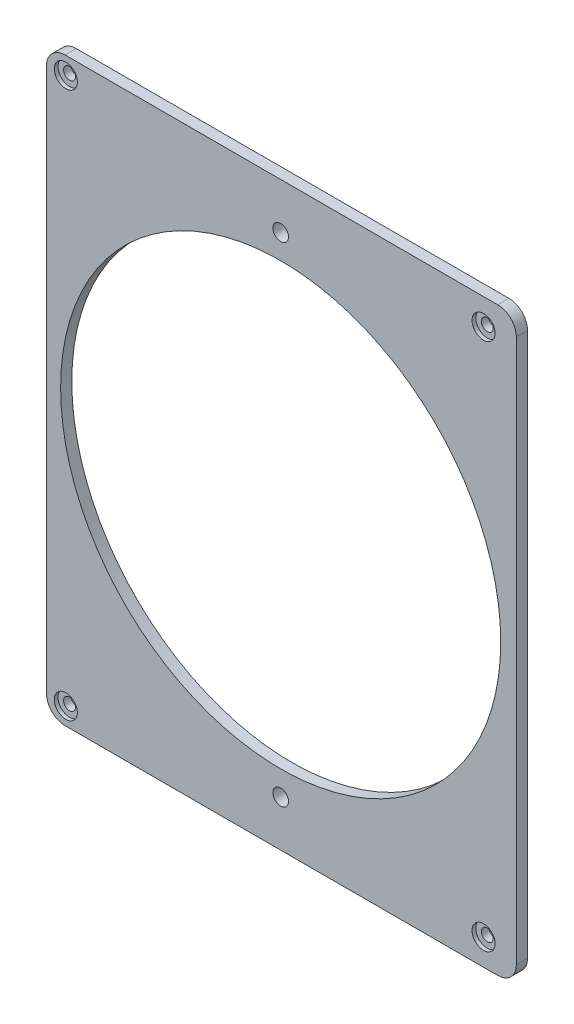
SolidWorks part; units mm, degrees
ref_plane "Front Plane" through (0, 0, 0) normal (0, 0, 1) x (1, 0, 0)
ref_plane "Top Plane" through (0, 0, 0) normal (0, 1, 0) x (1, 0, 0)
ref_plane "Right Plane" through (0, 0, 0) normal (1, 0, 0) x (0, 0, -1)
other "Configuration Table"
sketch "草图1" plane through (0, 0, 0) normal (0, 0, 1) x (1, 0, 0)
  line L0 (62.3, -78) -> (-53.9, -78)
  line L1 (67.3, -73) -> (67.3, 73)
  line L2 (62.3, 78) -> (-53.9, 78)
  line L3 (-58.9, -73) -> (-58.9, 73)
  line L4 (-57.3743, 76.5957) -> (-50.0357, 70.1007) construction
  line L5 (65.8355, 76.5355) -> (51.1514, 65.3931) construction
  line L6 (4, 0) -> (67.3, 0) construction
  circle A0 centre (4, 0) radius 59.1
  arc A1 (67.3, -73) -> (62.3, -78) centre (62.3, -73) cw
  arc A2 (-53.9, -78) -> (-58.9, -73) centre (-53.9, -73) cw
  arc A3 (67.3, 73) -> (62.3, 78) centre (62.3, 73) ccw
  arc A4 (-53.9, 78) -> (-58.9, 73) centre (-53.9, 73) ccw
  circle A7 centre (58.4934, 70.9643) radius 1.6
  circle A10 centre (-53.705, 73.3482) radius 1.6
  arc A11 (51.1, 64.5) -> (42.5, 75.1) centre (41.5, 65.5) ccw construction
  circle A12 centre (58.4934, -70.9643) radius 1.6
  circle A13 centre (-53.705, -73.3482) radius 1.6
  dimension "D1" = 118.2
extrude "凸台-拉伸1" add sketch "草图1" along normal blind 3
sketch "草图2" plane through (0, 0, 3) normal (0, 0, 1) x (1, 0, 0)
  line L0 (4, -59.1) -> (4, -72.2) construction
  line L1 (4, 59.1) -> (4, 72.2) construction
  circle A0 centre (4, -65.65) radius 2.1
  circle A1 centre (4, 65.65) radius 2.1
extrude "切除-拉伸1" cut sketch "草图2" against normal through all
sketch "草图3" plane through (0, 0, 3) normal (0, 0, 1) x (1, 0, 0)
  line L0 (4, 0) -> (16.8126, 0) construction
  circle A0 centre (58.4934, -70.9643) radius 3.1
  circle A1 centre (-53.705, -73.3482) radius 3.1
  circle A2 centre (-53.705, 73.3482) radius 3.1
  circle A3 centre (58.4934, 70.9643) radius 3.1
extrude "切除-拉伸2" cut sketch "草图3" against normal blind 1
